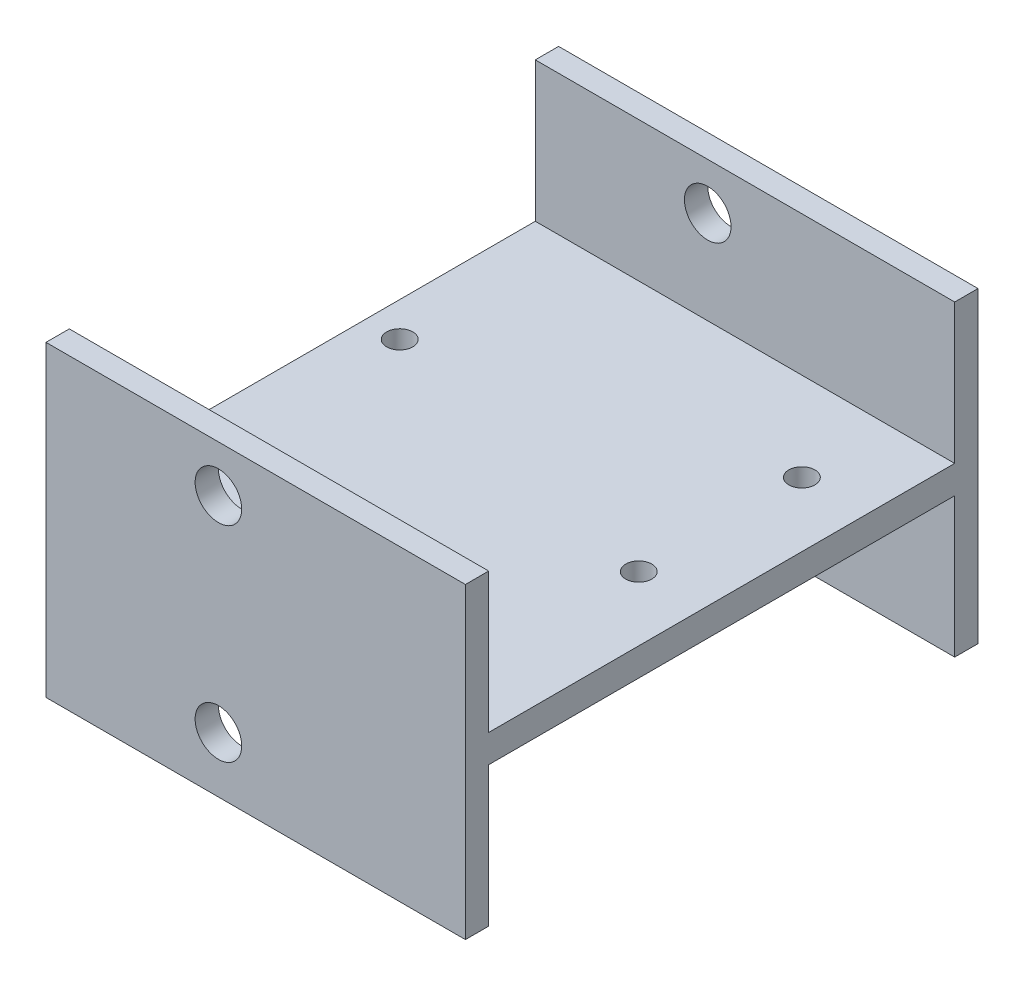
SolidWorks part; units mm, degrees
ref_plane "Plan de face" through (0, 0, 0) normal (0, 0, 1) x (1, 0, 0)
ref_plane "Plan de dessus" through (0, 0, 0) normal (0, 1, 0) x (1, 0, 0)
ref_plane "Plan de droite" through (0, 0, 0) normal (1, 0, 0) x (0, 0, -1)
sketch "Esquisse1" plane through (0, 0, 0) normal (0, 0, 1) x (1, 0, 0)
  line L1 (-3.0738, 3.7254) -> (41.9262, 3.7254)
  line L2 (-3.0738, 3.7254) -> (-3.0738, 0.7254)
  line L3 (-3.0738, 0.7254) -> (41.9262, 0.7254)
  line L4 (41.9262, 3.7254) -> (41.9262, 0.7254)
  dimension "D1" = 3
  dimension "D2" = 45
extrude "Boss.-Extru.1" add sketch "Esquisse1" along normal blind 55
sketch "Esquisse2" plane through (0, 0.7254, 0) normal (0, -1, 0) x (1, 0, 0)
  line L0 (-3.0738, 20.75) -> (41.9262, 20.75) construction
  line L1 (-3.0738, 55) -> (-3.0738, 0) construction
  line L2 (41.9262, 55) -> (41.9262, 0) construction
  line L3 (-3.0738, 0) -> (41.9262, 0) construction
  line L4 (35.0262, 29.5) -> (35.0262, 12) construction
  line L5 (19.4262, 55) -> (19.4262, 0) construction
  line L6 (-3.0738, 55) -> (41.9262, 55) construction
  circle A0 centre (0.6262, 20.75) radius 1.4
  circle A1 centre (35.0262, 12) radius 1.4
  circle A2 centre (35.0262, 29.5) radius 1.4
  dimension "D1" = 20.75
  dimension "D2" = 34.4
  dimension "D3" = 15.6
  dimension "D4" = 17.5
  dimension "D5" = 12
extrude "Enlèv. mat.-Extru.1" cut sketch "Esquisse2" against normal blind 50
sketch "Esquisse3" plane through (0, 0.7254, 0) normal (0, -1, 0) x (1, 0, 0)
  line L0 (41.9262, 55) -> (41.9262, 0) construction
  line L1 (-3.0738, 55) -> (41.9262, 55)
  line L2 (-3.0738, 55) -> (-3.0738, 52.5)
  line L3 (-3.0738, 52.5) -> (41.9262, 52.5)
  line L4 (41.9262, 55) -> (41.9262, 52.5)
  line L6 (-3.0738, 0) -> (41.9262, 0)
  line L7 (-3.0738, 0) -> (-3.0738, 2.5)
  line L8 (-3.0738, 2.5) -> (41.9262, 2.5)
  line L9 (41.9262, 0) -> (41.9262, 2.5)
  dimension "D1" = 2.5
  dimension "D2" = 2.5
extrude "Boss.-Extru.2" add sketch "Esquisse3" along normal blind 15
sketch "Esquisse4" plane through (0, 0, 55) normal (0, 0, 1) x (1, 0, 0)
  line L0 (15.4262, -14.2746) -> (15.4262, 3.7254) construction
  line L2 (41.9262, 3.7254) -> (-3.0738, 3.7254) construction
  line L6 (-3.0738, 3.7254) -> (-3.0738, -14.2746) construction
  circle A0 centre (15.4262, -8.2746) radius 2.5
  dimension "D1" = 12
  dimension "D3" = 5
  dimension "D2" = 18.5
extrude "Enlèv. mat.-Extru.2" cut sketch "Esquisse4" against normal blind 65
sketch "Esquisse5" plane through (0, 3.7254, 0) normal (0, 1, 0) x (1, 0, 0)
  line L0 (-3.0738, -55) -> (-3.0738, 0) construction
  line L1 (41.9262, -55) -> (-3.0738, -55)
  line L2 (41.9262, -55) -> (41.9262, -52.5)
  line L3 (41.9262, -52.5) -> (-3.0738, -52.5)
  line L4 (-3.0738, -55) -> (-3.0738, -52.5)
  line L6 (41.9262, 0) -> (-3.0738, 0)
  line L7 (41.9262, 0) -> (41.9262, -2.5)
  line L8 (41.9262, -2.5) -> (-3.0738, -2.5)
  line L9 (-3.0738, 0) -> (-3.0738, -2.5)
  dimension "D1" = 2.5
  dimension "D2" = 2.5
extrude "Boss.-Extru.3" add sketch "Esquisse5" along normal blind 15
sketch "Esquisse6" plane through (0, 0, 55) normal (0, 0, 1) x (1, 0, 0)
  line L0 (15.4262, -14.2746) -> (15.4262, 18.7254) construction
  line L3 (15.4262, -8.2746) -> (15.4262, 18.7254) construction
  line L4 (-3.0738, 18.7254) -> (41.9262, 18.7254) construction
  circle A0 centre (15.4262, 13.7254) radius 2.5
  circle A1 centre (15.4262, -8.2746) radius 2.5 construction
  dimension "D1" = 22
  dimension "D2" = 0
extrude "Enlèv. mat.-Extru.3" cut sketch "Esquisse6" against normal blind 65
